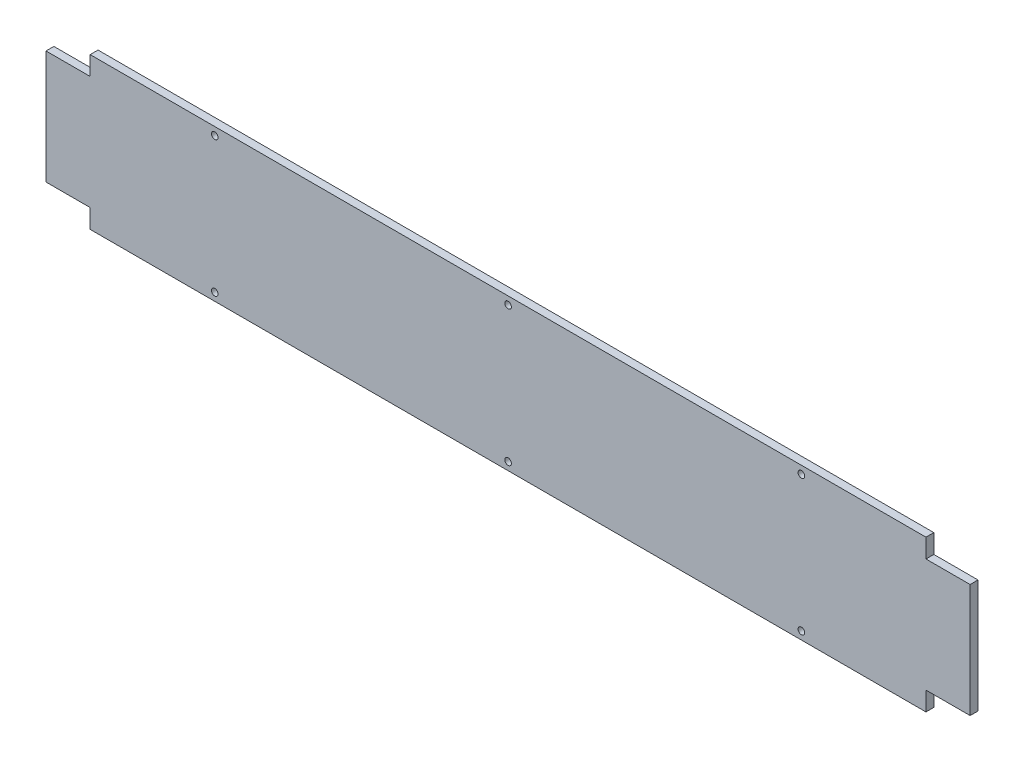
SolidWorks part; units mm, degrees
ref_plane "Front Plane" through (0, 0, 0) normal (0, 0, 1) x (1, 0, 0)
ref_plane "Top Plane" through (0, 0, 0) normal (0, 1, 0) x (1, 0, 0)
ref_plane "Right Plane" through (0, 0, 0) normal (1, 0, 0) x (0, 0, -1)
sketch "Sketch1" plane through (0, 0, 0) normal (0, 0, 1) x (1, 0, 0)
  line L9 (0, 0) -> (530, 0)
  line L10 (0, 0) -> (0, 96)
  line L11 (0, 96) -> (530, 96)
  line L12 (530, 0) -> (530, 96)
  dimension "D1" = 96
  dimension "D2" = 530
extrude "Boss-Extrude1" add sketch "Sketch1" along normal blind 5
sketch "Sketch2" plane through (0, 0, 5) normal (0, 0, 1) x (1, 0, 0)
  line L0 (0, 96) -> (0, 0) construction
  line L3 (530, 96) -> (0, 96) construction
  line L4 (32.0519, 48) -> (507.2554, 48) construction
  circle A0 centre (79, 91) radius 2.1
  circle A1 centre (265, 91) radius 2.1
  circle A2 centre (451, 91) radius 2.1
  circle A3 centre (451, 5) radius 2.1
  circle A4 centre (265, 5) radius 2.1
  circle A5 centre (79, 5) radius 2.1
  dimension "D1" = 4.2
  dimension "D2" = 4.2
  dimension "D3" = 4.2
  dimension "D6" = 186
  dimension "D4" = 79
  dimension "D5" = 186
  dimension "D7" = 5
  dimension "D8" = 48
extrude "Cut-Extrude1" cut sketch "Sketch2" against normal blind 5
sketch "Sketch3" plane through (0, 0, 5) normal (0, 0, 1) x (1, 0, 0)
  line L0 (530, 0) -> (530, 96) construction
  line L1 (530, 84) -> (558, 84)
  line L2 (530, 84) -> (530, 12)
  line L3 (530, 12) -> (558, 12)
  line L4 (558, 84) -> (558, 12)
  line L5 (0, 96) -> (0, 0) construction
  line L6 (0, 84) -> (-28, 84)
  line L7 (0, 84) -> (0, 12)
  line L8 (0, 12) -> (-28, 12)
  line L9 (-28, 84) -> (-28, 12)
  line L10 (530, 96) -> (0, 96) construction
  line L11 (0, 0) -> (530, 0) construction
  dimension "D1" = 12
  dimension "D2" = 28
  dimension "D3" = 12
  dimension "D4" = 12
  dimension "D5" = 12
  dimension "D6" = 28
extrude "Boss-Extrude2" add sketch "Sketch3" against normal blind 5
